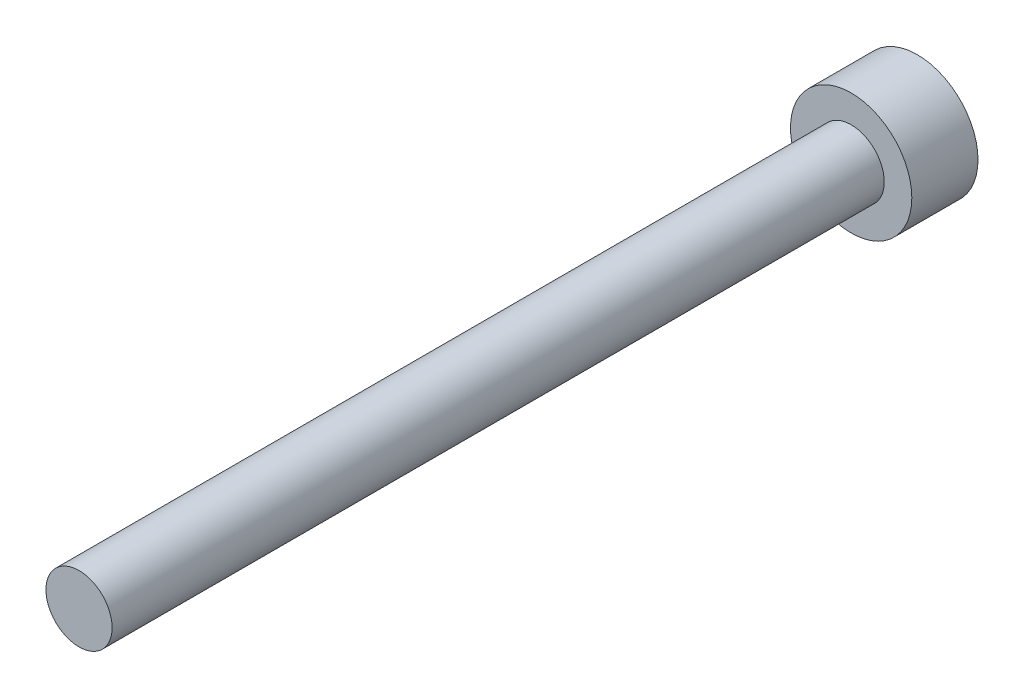
SolidWorks part; units mm, degrees
material "Acero aleado"
ref_plane "Alzado" through (0, 0, 0) normal (0, 0, 1) x (1, 0, 0)
ref_plane "Planta" through (0, 0, 0) normal (0, 1, 0) x (1, 0, 0)
ref_plane "Vista lateral" through (0, 0, 0) normal (1, 0, 0) x (0, 0, -1)
sketch "Croquis1" plane through (0, 0, 0) normal (0, 0, 1) x (1, 0, 0)
  circle A0 centre (0, 0) radius 2.75
  dimension "D1" = 5.5
extrude "Cabeza" add sketch "Croquis1" along normal blind 3 from offset 3
sketch "Croquis2" plane through (0, 0, 0) normal (0, 0, 1) x (1, 0, 0)
  circle A0 centre (0, 0) radius 1.5
  dimension "D1" = 3
extrude "Cuerpo" add sketch "Croquis2" along normal blind 35
sketch "Croquis3" plane through (0, 0, 0) normal (0, 0, 1) x (1, 0, 0)
  line L0 (1.4434, 0) -> (0.7217, 1.25)
  line L1 (0.7217, 1.25) -> (-0.7217, 1.25)
  line L2 (-0.7217, 1.25) -> (-1.4434, 0)
  line L3 (-1.4434, 0) -> (-0.7217, -1.25)
  line L4 (-0.7217, -1.25) -> (0.7217, -1.25)
  line L5 (0.7217, -1.25) -> (1.4434, 0)
  dimension "D1" = 1.4434
  dimension "D2" = 0.7217
  dimension "D3" = 1.25
  dimension "D4" = 0.7217
  dimension "D5" = 1.25
  dimension "D6" = 1.4434
  dimension "D7" = 0.7217
  dimension "D8" = 1.25
  dimension "D9" = 0.7217
  dimension "D10" = 1.25
extrude "Hexagono_interior" cut sketch "Croquis3" along normal blind 1.3 from offset 3
